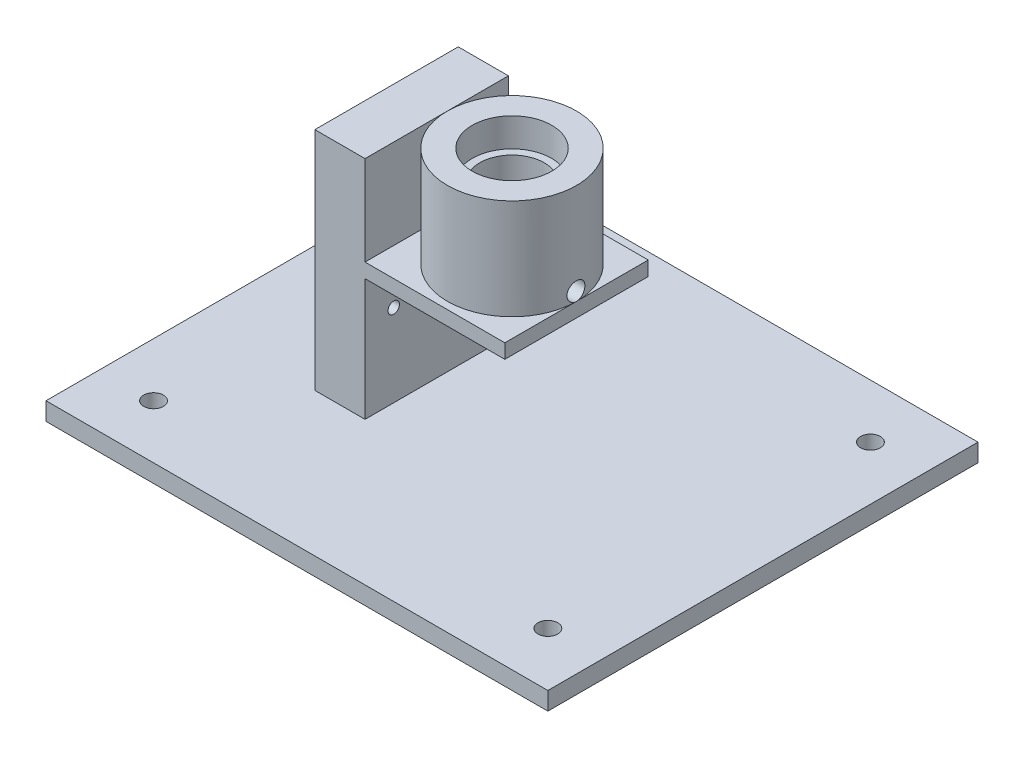
SolidWorks part; units mm, degrees
ref_plane "Front Plane" through (0, 0, 0) normal (0, 0, 1) x (1, 0, 0)
ref_plane "Top Plane" through (0, 0, 0) normal (0, 1, 0) x (1, 0, 0)
ref_plane "Right Plane" through (0, 0, 0) normal (1, 0, 0) x (0, 0, -1)
sketch "Bench_footprint_140x120_profile" plane through (0, 0, 0) normal (0, 1, 0) x (1, 0, 0)
  line L1 (-70, -60) -> (70, -60)
  line L2 (-70, -60) -> (-70, 60)
  line L3 (-70, 60) -> (70, 60)
  line L4 (70, -60) -> (70, 60)
  dimension "D1" = 140
  dimension "D2" = 120
  dimension "D3" = 70
  dimension "D4" = 60
extrude "Bench_footprint_140x120" add sketch "Bench_footprint_140x120_profile" along normal blind 5
sketch "Backbone_profile" plane through (0, 0, 0) normal (0, 0, 1) x (1, 0, 0)
  line L1 (-35, 5) -> (-21, 5)
  line L2 (-35, 5) -> (-35, 68)
  line L3 (-35, 68) -> (-21, 68)
  line L4 (-21, 5) -> (-21, 68)
  dimension "D1" = 14
  dimension "D2" = 63
  dimension "D3" = 21
  dimension "D4" = 5
extrude "Backbone" add sketch "Backbone_profile" along normal blind 40 from offset 20
sketch "Removable_servo_mount_M3_profile" plane through (0, 0, 0) normal (1, 0, 0) x (0, 0, -1)
  circle A0 centre (12, 28) radius 1.6
  circle A1 centre (-12, 28) radius 1.6
  dimension "D1" = 3.2
  dimension "D2" = 3.2
  dimension "D3" = 12
  dimension "D4" = 12
  dimension "D5" = 28
extrude "Removable_servo_mount_M3" cut sketch "Removable_servo_mount_M3_profile" along normal through all from offset 40
sketch "Bearing_bridge_profile" plane through (0, 0, 0) normal (0, 1, 0) x (1, 0, 0)
  line L1 (-35, -20) -> (18, -20)
  line L2 (-35, -20) -> (-35, 20)
  line L3 (-35, 20) -> (18, 20)
  line L4 (18, -20) -> (18, 20)
  dimension "D1" = 53
  dimension "D2" = 40
  dimension "D3" = 18
  dimension "D4" = 20
extrude "Bearing_bridge" add sketch "Bearing_bridge_profile" along normal blind 4 from offset 39
sketch "Bridge_horn_clearance_profile" plane through (0, 0, 0) normal (0, 1, 0) x (1, 0, 0)
  circle A0 centre (0, 0) radius 14
  dimension "D1" = 28
extrude "Bridge_horn_clearance" cut sketch "Bridge_horn_clearance_profile" along normal through all from offset 38
sketch "Drive_collar_chamber_profile" plane through (0, 0, 0) normal (0, 1, 0) x (1, 0, 0)
  circle A0 centre (0, 0) radius 18
  circle A1 centre (0, 0) radius 14
  dimension "D1" = 36
  dimension "D2" = 28
extrude "Drive_collar_chamber" add sketch "Drive_collar_chamber_profile" along normal blind 5 from offset 43
sketch "Bearing_tower_profile" plane through (0, 0, 0) normal (0, 1, 0) x (1, 0, 0)
  circle A0 centre (0, 0) radius 18
  circle A1 centre (0, 0) radius 11.1
  dimension "D1" = 36
  dimension "D2" = 22.2
extrude "Bearing_tower" add sketch "Bearing_tower_profile" along normal blind 23 from offset 48
sketch "Bearing_separation_shoulder_profile" plane through (0, 0, 0) normal (0, 1, 0) x (1, 0, 0)
  circle A0 centre (0, 0) radius 11.1
  circle A1 centre (0, 0) radius 9
  dimension "D1" = 22.2
  dimension "D2" = 18
extrude "Bearing_separation_shoulder" add sketch "Bearing_separation_shoulder_profile" along normal blind 8 from offset 55
sketch "Bench_clamp_holes_profile" plane through (0, 0, 0) normal (0, 1, 0) x (1, 0, 0)
  circle A0 centre (-55, -45) radius 2.75
  circle A1 centre (55, -45) radius 2.75
  circle A2 centre (-55, 45) radius 2.75
  circle A3 centre (55, 45) radius 2.75
  dimension "D1" = 5.5
  dimension "D2" = 5.5
  dimension "D3" = 5.5
  dimension "D4" = 5.5
  dimension "D5" = 55
  dimension "D6" = 55
  dimension "D7" = 45
  dimension "D8" = 45
extrude "Bench_clamp_holes" cut sketch "Bench_clamp_holes_profile" along normal through all from offset 1
sketch "Yaw_crossbolt_access_profile" plane through (0, 0, 0) normal (1, 0, 0) x (0, 0, -1)
  circle A0 centre (0, 45.5) radius 2.5
  dimension "D1" = 5
  dimension "D2" = 45.5
extrude "Yaw_crossbolt_access" cut sketch "Yaw_crossbolt_access_profile" along normal through all from offset 40
